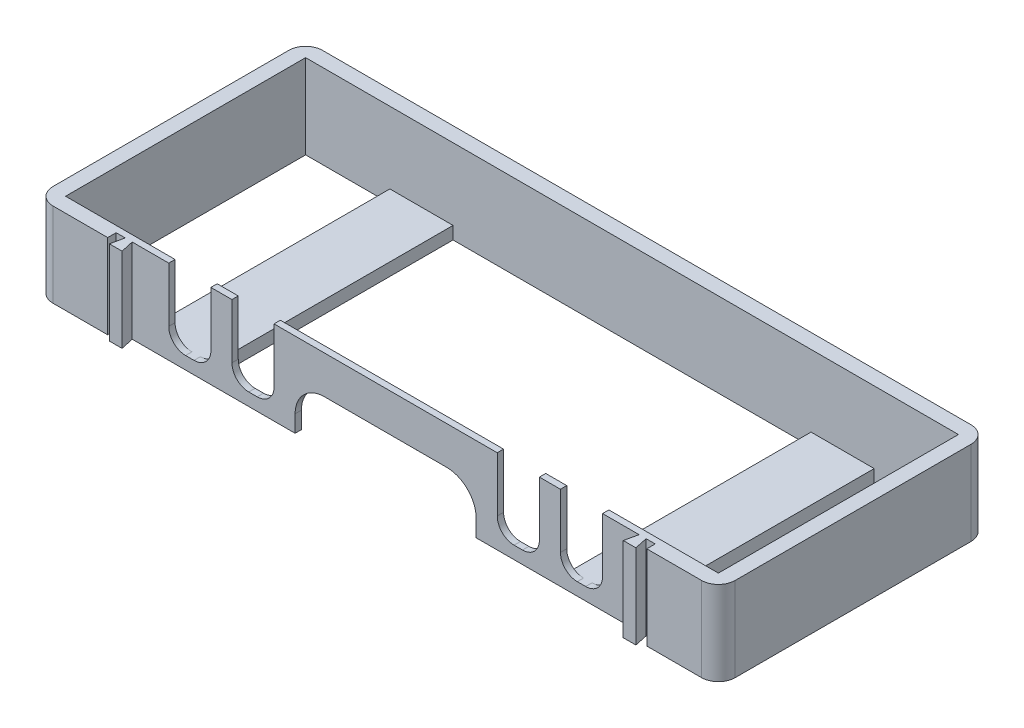
SolidWorks part; units mm, degrees
ref_plane "Front Plane" through (0, 0, 0) normal (0, 0, 1) x (1, 0, 0)
ref_plane "Top Plane" through (0, 0, 0) normal (0, 1, 0) x (1, 0, 0)
ref_plane "Right Plane" through (0, 0, 0) normal (1, 0, 0) x (0, 0, -1)
sketch "Sketch1" plane through (0, 0, 0) normal (0, 1, 0) x (1, 0, 0)
  line L1 (-126.5562, -76.2388) -> (-45.5562, -76.2388)
  line L2 (-126.5562, -76.2388) -> (-126.5562, -44.2388)
  line L3 (-126.5562, -44.2388) -> (-45.5562, -44.2388)
  line L4 (-45.5562, -76.2388) -> (-45.5562, -44.2388)
  dimension "D1" = 81
  dimension "D2" = 32
extrude "Boss-Extrude1" add sketch "Sketch1" along normal blind 10
sketch "Sketch2" plane through (0, 10, 0) normal (0, 1, 0) x (1, 0, 0)
  line L0 (-126.5562, -44.2388) -> (-126.5562, -76.2388) construction
  line L1 (-124.8062, -45.9888) -> (-47.3062, -45.9888)
  line L2 (-124.8062, -45.9888) -> (-124.8062, -74.4888)
  line L3 (-124.8062, -74.4888) -> (-47.3062, -74.4888)
  line L4 (-47.3062, -45.9888) -> (-47.3062, -74.4888)
  line L5 (-45.5562, -44.2388) -> (-126.5562, -44.2388) construction
  line L6 (-45.5562, -76.2388) -> (-45.5562, -44.2388) construction
  line L7 (-126.5562, -76.2388) -> (-45.5562, -76.2388) construction
  dimension "D1" = 1.75
  dimension "D2" = 1.75
  dimension "D3" = 1.75
  dimension "D4" = 1.75
extrude "Cut-Extrude1" cut sketch "Sketch2" against normal blind 10
sketch "Sketch3" plane through (0, 0, 0) normal (0, -1, 0) x (-1, 0, 0)
  line L0 (45.5562, -44.2388) -> (126.5562, -44.2388) construction
  line L1 (57.3062, -44.2388) -> (64.8062, -44.2388)
  line L2 (57.3062, -44.2388) -> (57.3062, -76.2388)
  line L3 (57.3062, -76.2388) -> (64.8062, -76.2388)
  line L4 (64.8062, -44.2388) -> (64.8062, -76.2388)
  line L5 (126.5562, -76.2388) -> (45.5562, -76.2388) construction
  line L6 (124.8062, -45.9888) -> (124.8062, -74.4888) construction
  line L7 (107.3062, -44.2388) -> (114.8062, -44.2388)
  line L8 (107.3062, -44.2388) -> (107.3062, -76.2388)
  line L9 (107.3062, -76.2388) -> (114.8062, -76.2388)
  line L10 (114.8062, -44.2388) -> (114.8062, -76.2388)
  line L11 (47.3062, -74.4888) -> (47.3062, -45.9888) construction
  dimension "D1" = 7.5
  dimension "D2" = 7.5
  dimension "D3" = 10
  dimension "D4" = 10
extrude "Boss-Extrude2" add sketch "Sketch3" against normal blind 1.5
sketch "Sketch4" plane through (0, 10, 0) normal (0, 1, 0) x (1, 0, 0)
  line L0 (-126.5562, -76.2388) -> (-45.5562, -76.2388) construction
  line L1 (-118.0562, -76.2388) -> (-54.0562, -76.2388)
  line L2 (-118.0562, -76.2388) -> (-118.0562, -75.2388)
  line L3 (-118.0562, -75.2388) -> (-54.0562, -75.2388)
  line L4 (-54.0562, -76.2388) -> (-54.0562, -75.2388)
  line L5 (-45.5562, -76.2388) -> (-45.5562, -44.2388) construction
  line L7 (-124.8062, -74.4888) -> (-47.3062, -74.4888) construction
  dimension "D1" = 64
  dimension "D2" = 8.5
  dimension "D3" = 0.75
extrude "Cut-Extrude2" cut sketch "Sketch4" against normal blind 10
sketch "Sketch5" plane through (0, 10, 0) normal (0, 1, 0) x (1, 0, 0)
  line L0 (-116.9762, -75.2388) -> (-117.3062, -76.7818)
  line L1 (-117.3062, -76.7818) -> (-115.8062, -76.7818)
  line L2 (-115.8062, -76.7818) -> (-116.1462, -75.2388)
  line L3 (-116.1462, -75.2388) -> (-116.9762, -75.2388)
  line L4 (-54.0562, -75.2388) -> (-118.0562, -75.2388) construction
  point P2 (-116.5612, -75.2388)
  dimension "D1" = 0.75
  dimension "D2" = 0
  dimension "D3" = 1.08
  dimension "D4" = 1.5
  dimension "D5" = 0.83
  dimension "D6" = 1.58
extrude "Boss-Extrude3" add sketch "Sketch5" against normal blind 10
sketch "Sketch6" plane through (0, 10, 0) normal (0, 1, 0) x (1, 0, 0)
  line L0 (-55.9662, -75.2388) -> (-56.3062, -76.7818)
  line L1 (-54.0562, -75.2388) -> (-116.1462, -75.2388) construction
  line L2 (-56.3062, -76.7818) -> (-54.8062, -76.7818)
  line L3 (-54.8062, -76.7818) -> (-55.1362, -75.2388)
  line L4 (-55.1362, -75.2388) -> (-55.9662, -75.2388)
  dimension "D1" = 1.5
  dimension "D2" = 1.58
  dimension "D3" = 0.83
  dimension "D4" = 0.75
  dimension "D5" = 1.08
extrude "Boss-Extrude4" add sketch "Sketch6" against normal blind 10
fillet "Fillet1" radius 2 1 edges at (-126.5562, 5, 76.2388)
fillet "Fillet2" radius 2 1 edges at (-45.5562, 5, 76.2388)
fillet "Fillet3" radius 2 1 edges at (-45.5562, 5, 44.2388)
fillet "Fillet4" radius 2 1 edges at (-126.5562, 5, 44.2388)
sketch "Sketch7" plane through (0, 0, 75.2388) normal (0, 0, 1) x (1, 0, 0)
  line L0 (-55.9662, 10) -> (-116.1462, 10) construction
  line L1 (-111.8062, 10) -> (-106.8062, 10)
  line L2 (-111.8062, 10) -> (-111.8062, 3.5)
  line L3 (-109.8062, 1.5) -> (-108.8062, 1.5)
  line L4 (-106.8062, 10) -> (-106.8062, 3.5)
  line L5 (-118.0562, 0) -> (-118.0562, 10) construction
  line L6 (-65.3062, 10) -> (-60.3062, 10)
  line L7 (-65.3062, 10) -> (-65.3062, 3.5)
  line L8 (-63.3062, 1.5) -> (-62.3062, 1.5)
  line L9 (-60.3062, 10) -> (-60.3062, 3.5)
  line L10 (-54.0562, 0) -> (-54.0562, 10) construction
  line L11 (-55.9662, 0) -> (-116.1462, 0) construction
  line L13 (-104.3062, 10) -> (-99.3062, 10)
  line L14 (-104.3062, 10) -> (-104.3062, 3.5)
  line L15 (-102.3062, 1.5) -> (-101.3062, 1.5)
  line L16 (-99.3062, 10) -> (-99.3062, 3.5)
  line L17 (-72.8062, 10) -> (-67.8062, 10)
  line L18 (-72.8062, 10) -> (-72.8062, 3.5)
  line L19 (-70.8062, 1.5) -> (-69.8062, 1.5)
  line L20 (-67.8062, 10) -> (-67.8062, 3.5)
  arc A0 (-62.3062, 1.5) -> (-60.3062, 3.5) centre (-62.3062, 3.5) ccw
  arc A1 (-65.3062, 3.5) -> (-63.3062, 1.5) centre (-63.3062, 3.5) ccw
  arc A2 (-69.8062, 1.5) -> (-67.8062, 3.5) centre (-69.8062, 3.5) ccw
  arc A3 (-72.8062, 3.5) -> (-70.8062, 1.5) centre (-70.8062, 3.5) ccw
  arc A4 (-101.3062, 1.5) -> (-99.3062, 3.5) centre (-101.3062, 3.5) ccw
  arc A5 (-104.3062, 3.5) -> (-102.3062, 1.5) centre (-102.3062, 3.5) ccw
  arc A6 (-108.8062, 1.5) -> (-106.8062, 3.5) centre (-108.8062, 3.5) ccw
  arc A7 (-111.8062, 3.5) -> (-109.8062, 1.5) centre (-109.8062, 3.5) ccw
  point P26 (-60.3062, 1.5)
  point P29 (-65.3062, 1.5)
  point P32 (-67.8062, 1.5)
  point P35 (-72.8062, 1.5)
  point P38 (-99.3062, 1.5)
  point P41 (-104.3062, 1.5)
  point P44 (-106.8062, 1.5)
  point P47 (-111.8062, 1.5)
  dimension "D13" = 2
  dimension "D1" = 5
  dimension "D2" = 5
  dimension "D3" = 6.25
  dimension "D4" = 6.25
  dimension "D5" = 1.5
  dimension "D6" = 1.5
  dimension "D7" = 5
  dimension "D8" = 5
  dimension "D9" = 1.5
  dimension "D10" = 1.5
  dimension "D11" = 2.5
  dimension "D12" = 2.5
extrude "Cut-Extrude3" cut sketch "Sketch7" against normal blind 0.75
sketch "Sketch8" plane through (0, 0, 75.2388) normal (0, 0, 1) x (1, 0, 0)
  line L0 (-55.9662, 0) -> (-116.1462, 0) construction
  line L1 (-96.8062, 5.5) -> (-75.3062, 5.5)
  line L2 (-96.8062, 5.5) -> (-96.8062, 0)
  line L3 (-96.8062, 0) -> (-75.3062, 0)
  line L4 (-75.3062, 5.5) -> (-75.3062, 0)
  line L5 (-99.3062, 3.5) -> (-99.3062, 10) construction
  line L6 (-72.8062, 10) -> (-72.8062, 3.5) construction
  dimension "D1" = 5.5
  dimension "D2" = 2.5
  dimension "D3" = 2.5
extrude "Cut-Extrude4" cut sketch "Sketch8" against normal blind 0.75
fillet "Fillet5" radius 3.5 1 edges at (-96.8062, 5.5, 74.8638)
fillet "Fillet6" radius 3.5 1 edges at (-75.3062, 5.5, 74.8638)
